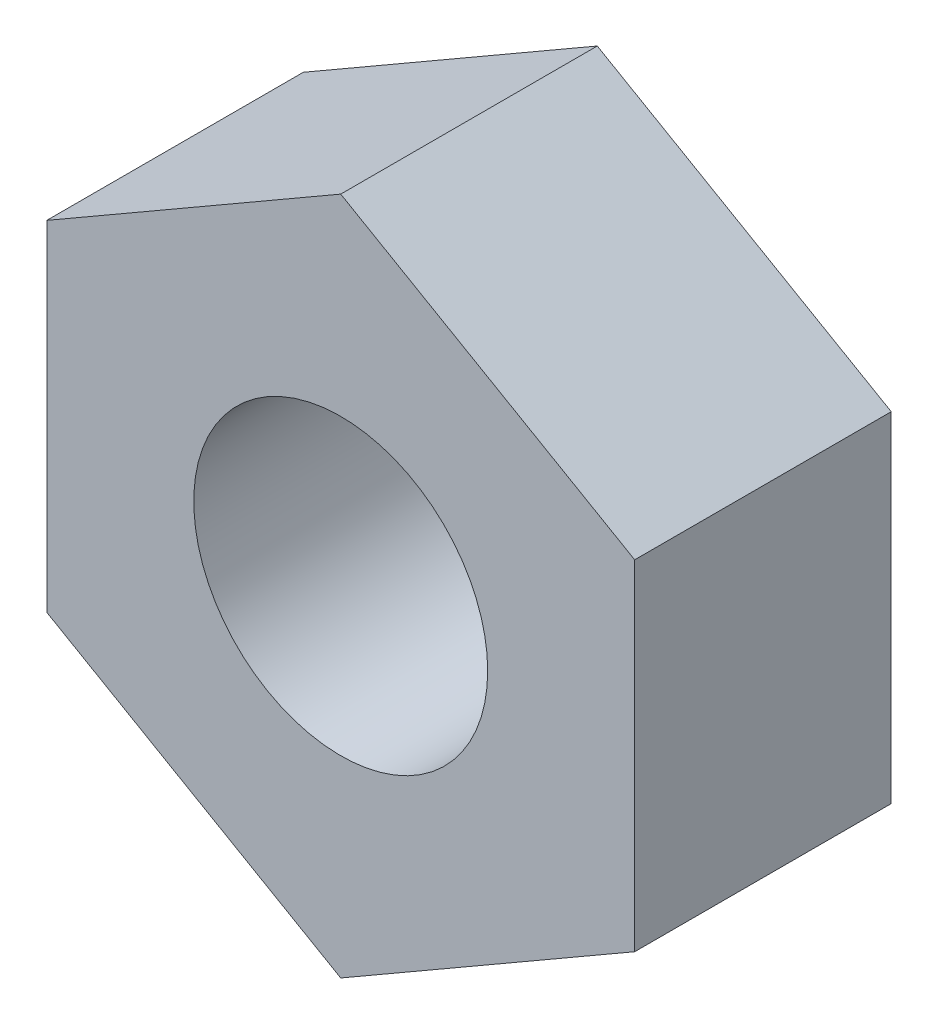
SolidWorks part; units mm, degrees
material "AISI 316 Stainless Steel Sheet (SS)"
ref_plane "Front Plane" through (0, 0, 0) normal (0, 0, 1) x (1, 0, 0)
ref_plane "Top Plane" through (0, 0, 0) normal (0, 1, 0) x (1, 0, 0)
ref_plane "Right Plane" through (0, 0, 0) normal (1, 0, 0) x (0, 0, -1)
sketch "Sketch1" plane through (0, 0, 0) normal (0, 0, 1) x (1, 0, 0)
  line L1 (2.75, -1.5877) -> (2.75, 1.5877)
  line L2 (2.75, 1.5877) -> (0, 3.1754)
  line L3 (0, 3.1754) -> (-2.75, 1.5877)
  line L4 (-2.75, 1.5877) -> (-2.75, -1.5877)
  line L5 (-2.75, -1.5877) -> (0, -3.1754)
  line L6 (0, -3.1754) -> (2.75, -1.5877)
  circle A0 centre (0, 0) radius 1.375
  circle A1 centre (0, 0) radius 2.75 construction
  dimension "D1" = 5.5
  dimension "D2" = 2.75
extrude "Boss-Extrude1" add sketch "Sketch1" along normal blind 2.4
